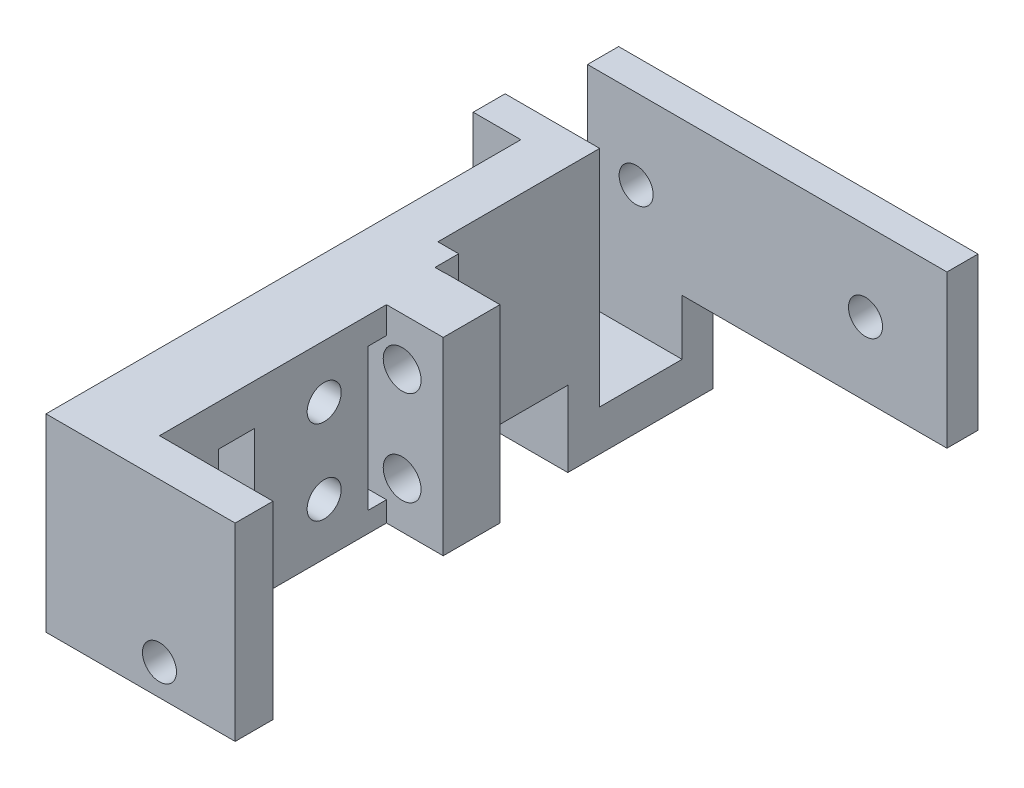
SolidWorks part; units mm, degrees
ref_plane "Front" through (0, 0, 0) normal (0, 0, 1) x (1, 0, 0)
ref_plane "Top" through (0, 0, 0) normal (0, 1, 0) x (1, 0, 0)
ref_plane "Right" through (0, 0, 0) normal (1, 0, 0) x (0, 0, -1)
sketch "Sketch1" plane through (0, 0, 0) normal (0, 1, 0) x (1, 0, 0)
  line L1 (0, 0) -> (8, 0)
  line L2 (0, 0) -> (0, -56.58)
  line L3 (0, -56.58) -> (8, -56.58)
  line L4 (8, 0) -> (8, -56.58)
  line L5 (0, -26.58) -> (14, -26.58)
  line L6 (0, -26.58) -> (0, -32.58)
  line L7 (0, -32.58) -> (14, -32.58)
  line L8 (14, -26.58) -> (14, -32.58)
  line L9 (0, -56.58) -> (20, -56.58)
  line L10 (0, -56.58) -> (0, -60.58)
  line L11 (0, -60.58) -> (20, -60.58)
  line L12 (20, -56.58) -> (20, -60.58)
  dimension "D1" = 24
  dimension "D2" = 6
  dimension "D3" = 6
  dimension "D4" = 8
  dimension "D5" = 4
  dimension "D6" = 20
  dimension "D7" = 56.58
extrude "Boss-Extrude1" add sketch "Sketch1" along normal blind 20 contours L7 L2 L3 L4 | L2 L7 L4 L5 | L2 L5 L4 L1 | L8 L5 L4 L7 | L12 L9 L3 L10 L11
sketch "Sketch2" plane through (0, 0, 0) normal (0, -1, 0) x (-1, 0, 0)
  line L0 (-7.4058, -24.1058) -> (-8.9058, -24.1058) construction
  line L1 (-8.1558, -24.1058) -> (-5.3536, -24.1058)
  line L2 (-8.1558, -24.1058) -> (-8.1558, 0.2442)
  line L3 (-8.1558, 0.2442) -> (-5.3536, 0.2442)
  line L4 (-5.3536, -24.1058) -> (-5.3536, 0.2442)
  line L6 (-8.1558, -24.1058) -> (-7.1558, -24.1058)
  line L7 (-8.1558, -24.1058) -> (-8.1558, -26.6058)
  line L8 (-8.1558, -26.6058) -> (-7.1558, -26.6058)
  line L9 (-7.1558, -24.1058) -> (-7.1558, -26.6058)
  line L10 (-5.3536, 0.2442) -> (-4.9638, 0.2442)
  line L11 (-5.3536, 0.2442) -> (-5.3536, -24.1058)
  line L12 (-5.3536, -24.1058) -> (-4.9638, -24.1058)
  line L13 (-4.9638, 0.2442) -> (-4.9638, -24.1058)
  line M6 (0, 0) -> (-8, 0)
  line M7 (-8, 0) -> (-8, -26.58)
  line M8 (-8, -26.58) -> (-14, -26.58)
  dimension "D1" = 2.5
  dimension "D2" = 1
extrude "Cut-Extrude1" cut sketch "Sketch2" against normal blind 20 contours L9 L1 L7 L8 M7 M8 | L1 L4 M6 M7 | L13 L4 L12 M6
sketch "Sketch3" plane through (0, 0, 0) normal (0, 0, -1) x (-1, 0, 0)
  line L1 (19.612, -22.3932) -> (-22.8928, -22.3932)
  line L2 (19.612, -22.3932) -> (19.612, 38.8779)
  line L3 (19.612, 38.8779) -> (-22.8928, 38.8779)
  line L4 (-22.8928, -22.3932) -> (-22.8928, 38.8779)
extrude "Cut-Extrude2" cut sketch "Sketch3" against normal blind 7
sketch "Sketch5" plane through (0, 0, 0) normal (0, -1, 0) x (-1, 0, 0)
  line L1 (-4.9638, -7) -> (5.0362, -7)
  line L2 (-4.9638, -7) -> (-4.9638, -10.373)
  line L3 (-4.9638, -10.373) -> (5.0362, -10.373)
  line L4 (5.0362, -7) -> (5.0362, -10.373)
extrude "Boss-Extrude3" add sketch "Sketch5" against normal blind 20 and the other way blind 8
sketch "Sketch6" plane through (0, 0, 26.58) normal (0, 0, -1) x (-1, 0, 0)
  circle A0 centre (-9.6558, 4.9046) radius 2
  circle A1 centre (-9.6558, 14.9046) radius 2
extrude "Cut-Extrude3" cut sketch "Sketch6" against normal blind 6
sketch "Sketch7" plane through (0, 0, 7) normal (0, 0, -1) x (-1, 0, 0)
  line L0 (5.0362, -8) -> (5.0362, 20) construction
  line L1 (-4.9638, -8) -> (5.0362, -8)
  line L2 (-4.9638, -8) -> (-4.9638, -3.6743)
  line L3 (-4.9638, -3.6743) -> (5.0362, -3.6743)
  line L4 (5.0362, -8) -> (5.0362, -3.6743)
extrude "Boss-Extrude4" add sketch "Sketch7" along normal blind 12
sketch "Sketch8" plane through (0, -3.6743, 0) normal (0, 1, 0) x (1, 0, 0)
  line L0 (-5.0362, 5) -> (-5.0362, -7) construction
  line L1 (4.9638, 5) -> (-5.0362, 5)
  line L2 (4.9638, 5) -> (4.9638, 1.7149)
  line L3 (4.9638, 1.7149) -> (-5.0362, 1.7149)
  line L4 (-5.0362, 5) -> (-5.0362, 1.7149)
extrude "Boss-Extrude5" add sketch "Sketch8" along normal blind 22
sketch "Sketch9" plane through (0, 0, -5) normal (0, 0, -1) x (-1, 0, 0)
  circle A0 centre (-0.1027, 9.8606) radius 1.8
extrude "Cut-Extrude4" cut sketch "Sketch9" against normal blind 20
sketch "Sketch10" plane through (0, 0, 0) normal (-1, 0, 0) x (0, 0, 1)
  line L0 (10.373, 0) -> (10.373, 8.0635) construction
  line L1 (10.373, 7) -> (15.0312, 7)
  line L2 (10.373, 7) -> (10.373, 12.7)
  line L3 (10.373, 12.7) -> (15.0312, 12.7)
  line L4 (15.0312, 7) -> (15.0312, 12.7)
  line L5 (10.373, 0) -> (60.58, 0) construction
  dimension "D1" = 5.7
  dimension "D2" = 7
extrude "Cut-Extrude5" cut sketch "Sketch10" against normal blind 3
sketch "Sketch12" plane through (0, 0, 60.58) normal (0, 0, 1) x (1, 0, 0)
  line L0 (20, 20) -> (20, 0) construction
  circle A0 centre (12, 3.2655) radius 1.8
  dimension "D1" = 8
extrude "Cut-Extrude7" cut sketch "Sketch12" against normal blind 5
sketch "Sketch13" plane through (0, 0, 0) normal (-1, 0, 0) x (0, 0, 1)
  circle A0 centre (39.1672, 5.4688) radius 1.8
  circle A1 centre (39.1672, 14.3708) radius 1.8
extrude "Cut-Extrude8" cut sketch "Sketch13" against normal blind 12
sketch "Sketch14" plane through (4.9638, 0, 0) normal (1, 0, 0) x (0, 0, -1)
  line L0 (5, 18.3257) -> (5, -8) construction
  line L1 (1.7149, 18.3257) -> (5, 18.3257)
  line L2 (1.7149, 18.3257) -> (1.7149, 2.185)
  line L3 (1.7149, 2.185) -> (5, 2.185)
  line L4 (5, 18.3257) -> (5, 2.185)
  dimension "D1" = 16.1407
extrude "Boss-Extrude6" add sketch "Sketch14" along normal blind 28
sketch "Sketch15" plane through (0, 0, -5) normal (0, 0, -1) x (-1, 0, 0)
  circle A0 centre (-24.3532, 9.9046) radius 1.8
extrude "Cut-Extrude9" cut sketch "Sketch15" against normal blind 20
sketch "Sketch16" plane through (8, 0, 0) normal (1, 0, 0) x (0, 0, -1)
  line L0 (-32.58, 20) -> (-32.58, 16.0264) construction
  line L1 (-32.58, 17.1649) -> (-34.5527, 17.1649)
  line L2 (-32.58, 17.1649) -> (-32.58, 2.1366)
  line L3 (-32.58, 2.1366) -> (-34.5527, 2.1366)
  line L4 (-34.5527, 17.1649) -> (-34.5527, 2.1366)
extrude "Cut-Extrude10" cut sketch "Sketch16" against normal blind 2
sketch "Sketch18" plane through (0, 0, 0) normal (-1, 0, 0) x (0, 0, 1)
  line L1 (46.5401, 4.9513) -> (50.3649, 4.9513)
  line L2 (46.5401, 4.9513) -> (46.5401, 15.6436)
  line L3 (46.5401, 15.6436) -> (50.3649, 15.6436)
  line L4 (50.3649, 4.9513) -> (50.3649, 15.6436)
extrude "Cut-Extrude11" cut sketch "Sketch18" against normal blind 10
